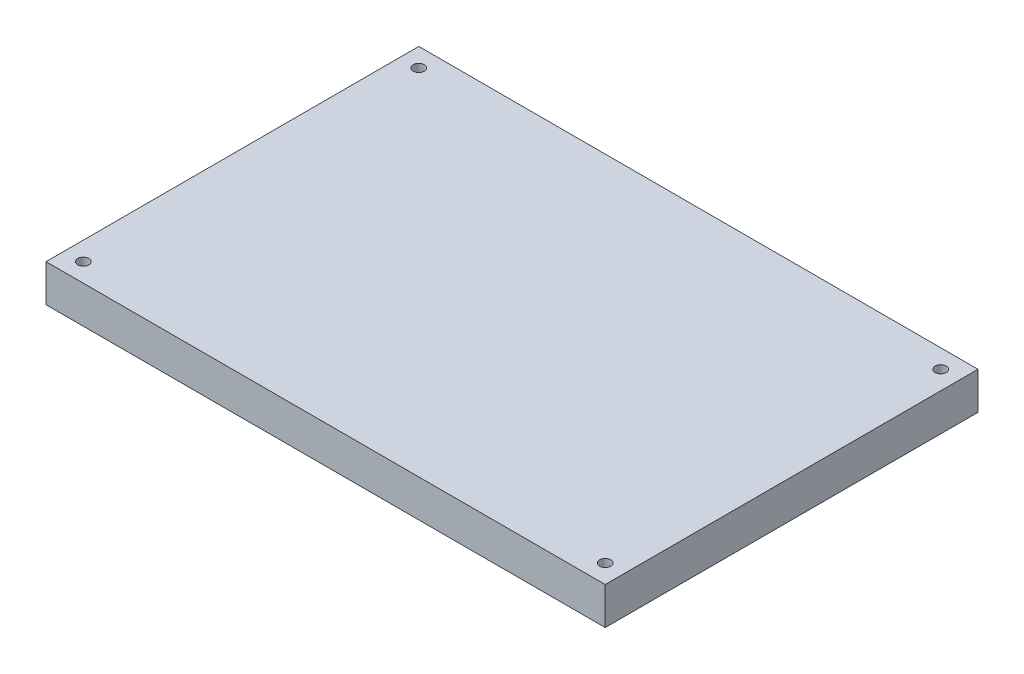
SolidWorks part; units mm, degrees
ref_plane "Front Plane" through (0, 0, 0) normal (0, 0, 1) x (1, 0, 0)
ref_plane "Top Plane" through (0, 0, 0) normal (0, 1, 0) x (1, 0, 0)
ref_plane "Right Plane" through (0, 0, 0) normal (1, 0, 0) x (0, 0, -1)
sketch "Sketch1" plane through (0, 0, 0) normal (0, 1, 0) x (1, 0, 0)
  line L1 (0, 0) -> (300, 0)
  line L2 (0, 0) -> (0, 200)
  line L3 (0, 200) -> (300, 200)
  line L4 (300, 0) -> (300, 200)
  dimension "D1" = 200
  dimension "D2" = 300
extrude "Boss-Extrude2" add sketch "Sketch1" along normal blind 20
sketch "Sketch3" [suppressed] plane through (0, 20, 0) normal (0, 1, 0) x (1, 0, 0)
  line L0 (0, 200) -> (0, 0) construction
  line L1 (300, 200) -> (0, 200) construction
  circle A0 centre (150, 100) radius 10
  dimension "D1" = 150
  dimension "D3" = 20
  dimension "D2" = 100
extrude "Cut-Extrude1" [suppressed] cut sketch "Sketch3" against normal blind 20
sketch "Sketch8" plane through (0, 20, 0) normal (0, 1, 0) x (1, 0, 0)
  line L0 (0, 200) -> (0, 0) construction
  line L1 (300, 200) -> (0, 200) construction
  circle A0 centre (10, 190) radius 3
  dimension "D1" = 6
  dimension "D2" = 10
  dimension "D3" = 10
extrude "Cut-Extrude14" cut sketch "Sketch8" against normal blind 20 contours A0
sketch "Sketch10" plane through (0, 20, 0) normal (0, 1, 0) x (1, 0, 0)
  line L0 (0, 0) -> (300, 0) construction
  line L1 (0, 200) -> (0, 0) construction
  circle A0 centre (10, 10) radius 3
  point P6 (-0.636, 9.0938)
  dimension "D1" = 6
  dimension "D2" = 10
  dimension "D3" = 10
extrude "Cut-Extrude16" cut sketch "Sketch10" against normal blind 20 contours A0
sketch "Sketch11" plane through (0, 20, 0) normal (0, 1, 0) x (1, 0, 0)
  line L0 (300, 0) -> (300, 200) construction
  line L1 (300, 200) -> (0, 200) construction
  line L2 (0, 0) -> (300, 0) construction
  circle A0 centre (290, 190) radius 3
  circle A1 centre (290, 10) radius 3
  dimension "D1" = 6
  dimension "D2" = 6
  dimension "D3" = 10
  dimension "D4" = 10
  dimension "D5" = 10
  dimension "D6" = 10
extrude "Cut-Extrude17" cut sketch "Sketch11" against normal blind 20
